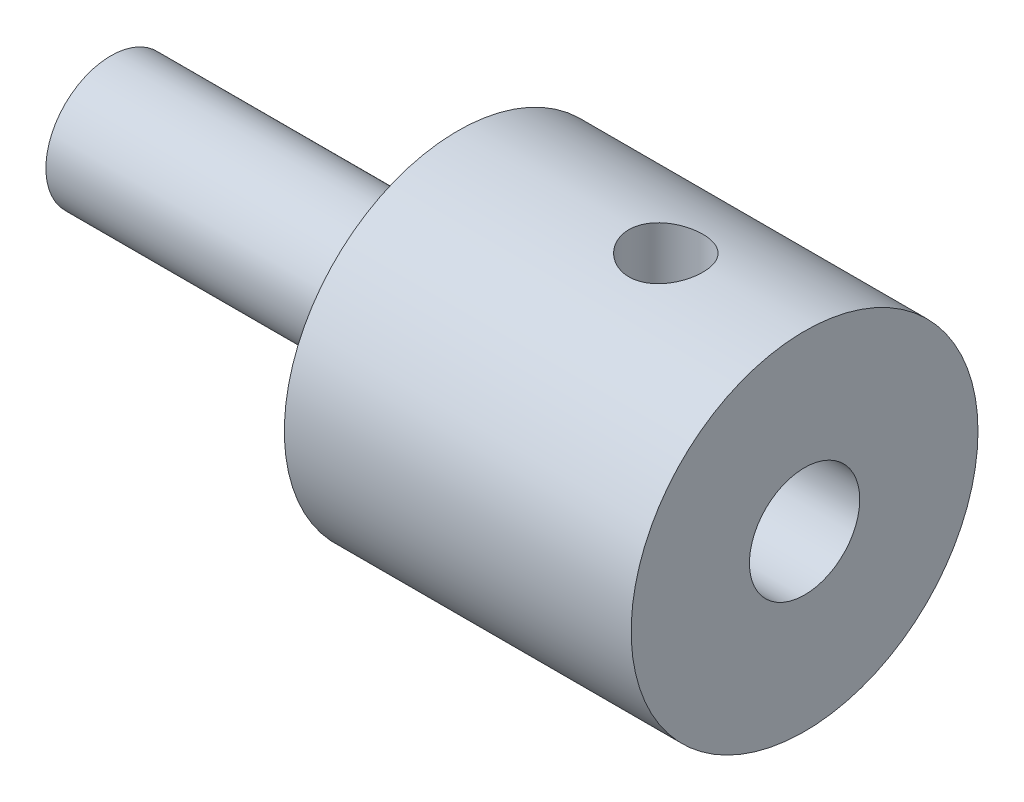
SolidWorks part; units mm, degrees
material "Plain Carbon Steel"
ref_plane "Front Plane" through (0, 0, 0) normal (0, 0, 1) x (1, 0, 0)
ref_plane "Top Plane" through (0, 0, 0) normal (0, 1, 0) x (1, 0, 0)
ref_plane "Right Plane" through (0, 0, 0) normal (1, 0, 0) x (0, 0, -1)
sketch "Sketch1" plane through (0, 0, 0) normal (1, 0, 0) x (0, 0, -1)
  circle A0 centre (0, 0) radius 6.35
  dimension "D1" = 12.7
extrude "Boss-Extrude1" add sketch "Sketch1" along normal blind 25.4
hole_wizard "#21 (0.159) Diameter Hole1" positions "Sketch4" profile "Sketch3" hole size "#21" standard "ANSI Inch"
sketch "Sketch4" plane through (25.4, 0, 0) normal (1, 0, 0) x (0, 0, -1)
  point P0 (0, 0)
sketch "Sketch3" plane through (25.4, 0, 0) normal (0, 1, 0) x (0, 0, -1)
  line L0 (0, 0) -> (0, 10.2133)
  line L1 (0, 10.2133) -> (2.0193, 9)
  line L2 (2.0193, 9) -> (2.0193, 0)
  line L5 (2.0193, 0) -> (0, 0)
  line L10 (0, 10.2133) -> (-2.0193, 9) construction
  line L11 (0, -6.35) -> (0, 107.95) construction
  dimension "Hole Dia." = 4.0386
  dimension "Hole Depth" = 9
  dimension "Drill Angle" = 118
hole_wizard "#6-32 Tapped Hole1" positions "Sketch6" profile "Sketch5" tap size "#6-32" standard "ANSI Inch"
sketch "Sketch6" plane through (0, 0, 0) normal (0, 1, 0) x (1, 0, 0)
  line L0 (25.4, -6.35) -> (25.4, 6.35) construction
  point P0 (20.32, 0)
  dimension "D1" = 5.08
sketch "Sketch5" plane through (20.32, 0, 0) normal (1, 0, 0) x (0, 0, -1)
  line L0 (0, 0) -> (0, 6.35)
  line L1 (0, 6.35) -> (1.3525, 6.35)
  line L2 (1.3525, 6.35) -> (1.3525, 0)
  line L5 (1.3525, 0) -> (0, 0)
  line L11 (0, -6.35) -> (0, 107.95) construction
  dimension "Thru Tap Drill Dia." = 2.7051
  dimension "Thru Tap Drill Depth" = 6.35
cosmetic thread "Hole Thread1" parameters "D2"=3.5052
sketch "Sketch7" plane through (0, 0, 0) normal (0, 1, 0) x (1, 0, 0)
  line L1 (0, 6.35) -> (12.7, 6.35)
  line L2 (0, 6.35) -> (0, 2.3813)
  line L3 (0, 2.3813) -> (12.7, 2.3813)
  line L4 (12.7, 6.35) -> (12.7, 2.3813)
  dimension "D1" = 12.7
  dimension "D2" = 2.3813
ref_axis "Axis1" through (25.4, 0, 0) along (-1, 0, 0)
revolve "Cut-Revolve1" cut sketch "Sketch7" angle 360 about axis through (25.4, 0, 0) along (-1, 0, 0)
